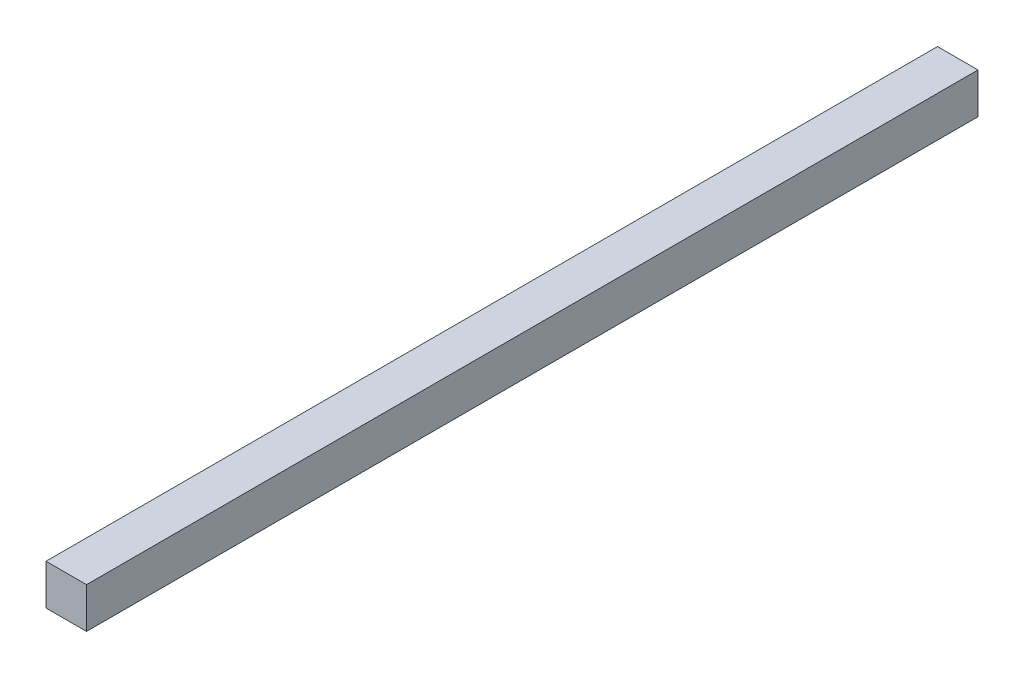
SolidWorks part; units mm, degrees
ref_plane "Front Plane" through (0, 0, 0) normal (0, 0, 1) x (1, 0, 0)
ref_plane "Top Plane" through (0, 0, 0) normal (0, 1, 0) x (1, 0, 0)
ref_plane "Right Plane" through (0, 0, 0) normal (1, 0, 0) x (0, 0, -1)
other "Configuration Table"
sketch "Sketch1" plane through (0, 0, 0) normal (0, 0, 1) x (1, 0, 0)
  line L1 (20, 1300) -> (40, 1300)
  line L2 (20, 1300) -> (20, 1320)
  line L3 (20, 1320) -> (40, 1320)
  line L4 (40, 1300) -> (40, 1320)
extrude "PRESS_kova_kizagi_sol_1" add sketch "Sketch1" against normal blind 440 from offset 60 separate body
